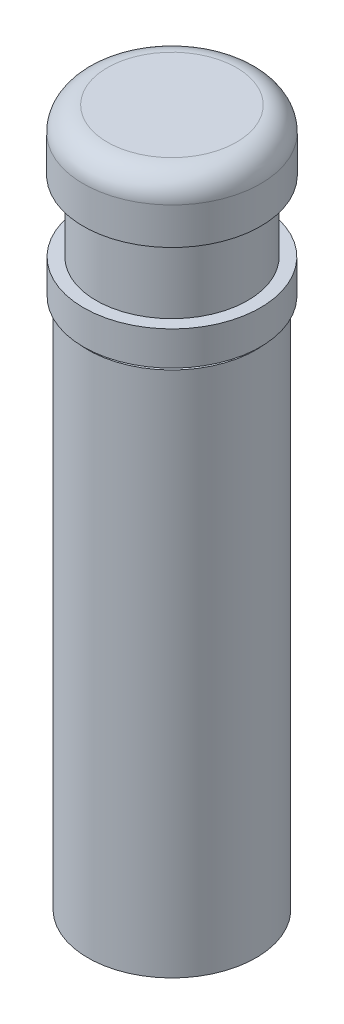
SolidWorks part; units mm, degrees
ref_plane "前视基准面" through (0, 0, 0) normal (0, 0, 1) x (1, 0, 0)
ref_plane "上视基准面" through (0, 0, 0) normal (0, 1, 0) x (1, 0, 0)
ref_plane "右视基准面" through (0, 0, 0) normal (1, 0, 0) x (0, 0, -1)
sketch "草图1" plane through (0, 0, 0) normal (1, 0, 0) x (0, 0, -1)
  line L0 (0, 0) -> (0, 93.9292) construction
  line L1 (-7, 0) -> (0, 0)
  line L2 (-5.3782, 58) -> (0, 58)
  line L3 (0, 58) -> (0, 0)
  line L4 (-7.3548, 44.2206) -> (-7.3548, 47.0483)
  line L16 (-7.3782, 52.9333) -> (-7.3782, 56)
  line L17 (-6.3094, 52.9333) -> (-7.3782, 52.9333)
  line L18 (-6.3094, 47.0483) -> (-6.3094, 52.9333)
  line L19 (-7.3548, 47.0483) -> (-6.3094, 47.0483)
  line L25 (-6.3094, 44.2206) -> (-7.3548, 44.2206)
  line L26 (-6.3094, 43.8356) -> (-6.3094, 44.2206)
  line L27 (-7, 43.8356) -> (-6.3094, 43.8356)
  line L28 (-7, 0) -> (-7, 43.8356)
  arc A0 (-5.3782, 58) -> (-7.3782, 56) centre (-5.3782, 56) ccw
  point P36 (-6.9141, 55.0317)
  dimension "D4" = 2
  dimension "D1" = 7
  dimension "D2" = 58
revolve "旋转4" add sketch "草图1" angle 360 about L0
